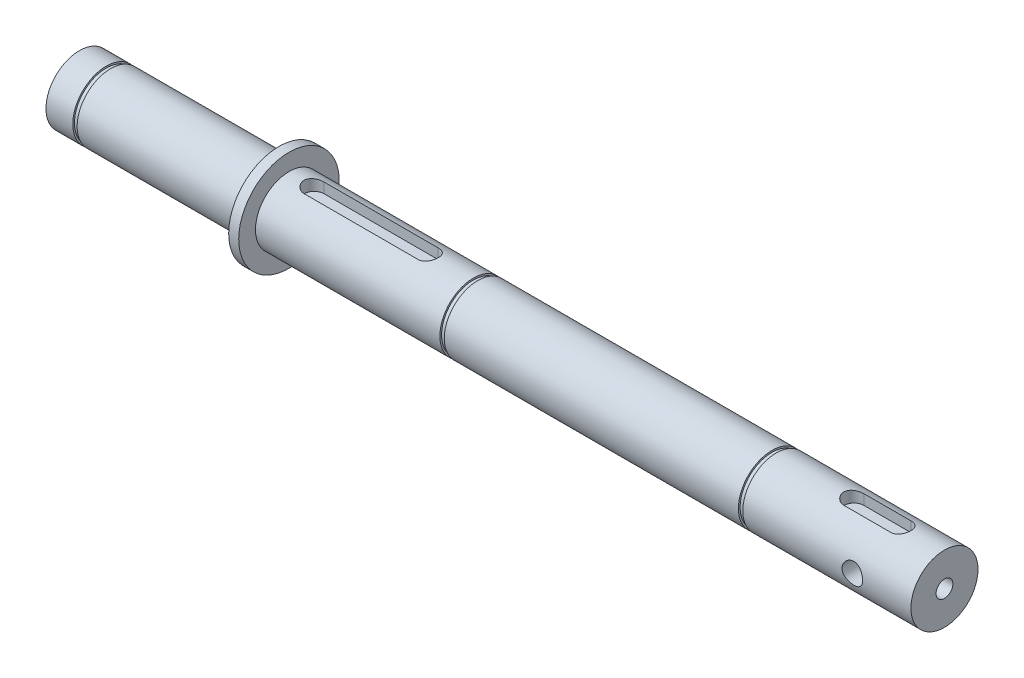
SolidWorks part; units mm, degrees
ref_plane "Alzado" through (0, 0, 0) normal (0, 0, 1) x (1, 0, 0)
ref_plane "Planta" through (0, 0, 0) normal (0, 1, 0) x (1, 0, 0)
ref_plane "Vista lateral" through (0, 0, 0) normal (1, 0, 0) x (0, 0, -1)
sketch "Croquis1" plane through (0, 0, 0) normal (1, 0, 0) x (0, 0, -1)
  circle A0 centre (0, 0) radius 10
  dimension "D1" = 20
extrude "Saliente-Extruir1" add sketch "Croquis1" along normal blind 258 from offset 8
ref_plane "Plano1" through (70.5, 0, 0) normal (-1, 0, 0) x (0, 0, 1)
sketch "Croquis2" plane through (70.5, 0, 0) normal (-1, 0, 0) x (0, 0, 1)
  circle A0 centre (0, 0) radius 15
  dimension "D1" = 30
extrude "Saliente-Extruir2" add sketch "Croquis2" along normal blind 3
sketch "Croquis3" plane through (0, 0, 0) normal (0, 0, 1) x (1, 0, 0)
  circle A0 centre (248.5, 0) radius 3.075
  dimension "D1" = 6.15
extrude "Cortar-Extruir1" cut sketch "Croquis3" against normal up to next and the other way up to next
sketch "Croquis4" plane through (0, 0, 0) normal (0, 1, 0) x (1, 0, 0)
  line L0 (266, 0) -> (231.4531, 0) construction
  line L1 (266, -10) -> (266, 10) construction
  line L2 (239, 0) -> (253, 0) construction
  line L3 (239, 3) -> (253, 3)
  line L4 (239, -3) -> (253, -3)
  arc A0 (239, 3) -> (239, -3) centre (239, 0) ccw
  arc A1 (253, -3) -> (253, 3) centre (253, 0) ccw
  point P7 (246, 0)
  dimension "D1" = 6
  dimension "D2" = 20
  dimension "D3" = 14
extrude "Cortar-Extruir2" cut sketch "Croquis4" against normal blind 3.5 from offset 10
hole_wizard "Taladro roscado M61" positions "Croquis3D2" profile "Croquis7" tap size "M6" standard "DIN"
sketch3d "Croquis3D2"
  circle A0 centre (266, 0, 0) radius 10 construction
  point P0 (266, 0, 0)
  point P5 (276, 0, 0)
sketch "Croquis7" plane through (266, 0, 0) normal (0, 1, 0) x (0, 0, -1)
  line L0 (0, 0) -> (0, 13)
  line L1 (0, 13) -> (2.5, 11.4978)
  line L2 (2.5, 11.4978) -> (2.5, 0)
  line L5 (2.5, 0) -> (0, 0)
  line L10 (0, 13) -> (-2.5, 11.4978) construction
  line L11 (0, -6.35) -> (0, 107.95) construction
  dimension "Diámetro de perforador para roscar" = 5
  dimension "Profundidad de perforador para roscar" = 13
  dimension "Ángulo de perforador" = 118
cosmetic thread "Rosca de taladro1" parameters "D1"=12, "D2"=6
sketch "Croquis8" plane through (0, 0, 0) normal (0, 1, 0) x (1, 0, 0)
  line L0 (8.3, 0) -> (274.8253, 0) construction
  line L1 (8.3, -21) -> (8.3, 21) construction
  line L2 (78, 0) -> (112, 0) construction
  line L3 (78, 3) -> (112, 3)
  line L4 (78, -3) -> (112, -3)
  line L5 (8, 10) -> (8, -10) construction
  arc A0 (78, 3) -> (78, -3) centre (78, 0) ccw
  arc A1 (112, -3) -> (112, 3) centre (112, 0) ccw
  point P7 (95, 0)
  point P14 (75, 0)
  point P15 (115, 0)
  dimension "D1" = 87
  dimension "D2" = 40
  dimension "D3" = 6
extrude "Cortar-Extruir3" cut sketch "Croquis8" against normal blind 3.5 from offset 10
sketch "Croquis9" plane through (0, 0, 0) normal (1, 0, 0) x (0, 0, -1)
  circle A0 centre (0, 0) radius 9.5
  circle A1 centre (0, 0) radius 10
  circle A2 centre (0, 0) radius 10 construction
  dimension "D1" = 19
extrude "Cortar-Extruir4" cut sketch "Croquis9" along normal blind 1.3 from offset 125.5
sketch "Croquis10" plane through (0, 0, 0) normal (1, 0, 0) x (0, 0, -1)
  circle A0 centre (0, 0) radius 9.5
  circle A1 centre (0, 0) radius 10
  circle A3 centre (0, 0) radius 10 construction
  dimension "D1" = 19
extrude "Cortar-Extruir5" cut sketch "Croquis10" against normal blind 1.3 from surface
sketch "Croquis11" plane through (8, 0, 0) normal (-1, 0, 0) x (0, 0, 1)
  circle A0 centre (0, 0) radius 9.5
  circle A1 centre (0, 0) radius 10
  circle A2 centre (0, 0) radius 10 construction
  dimension "D1" = 19
extrude "Cortar-Extruir6" cut sketch "Croquis11" against normal blind 1.3 from surface at -8
